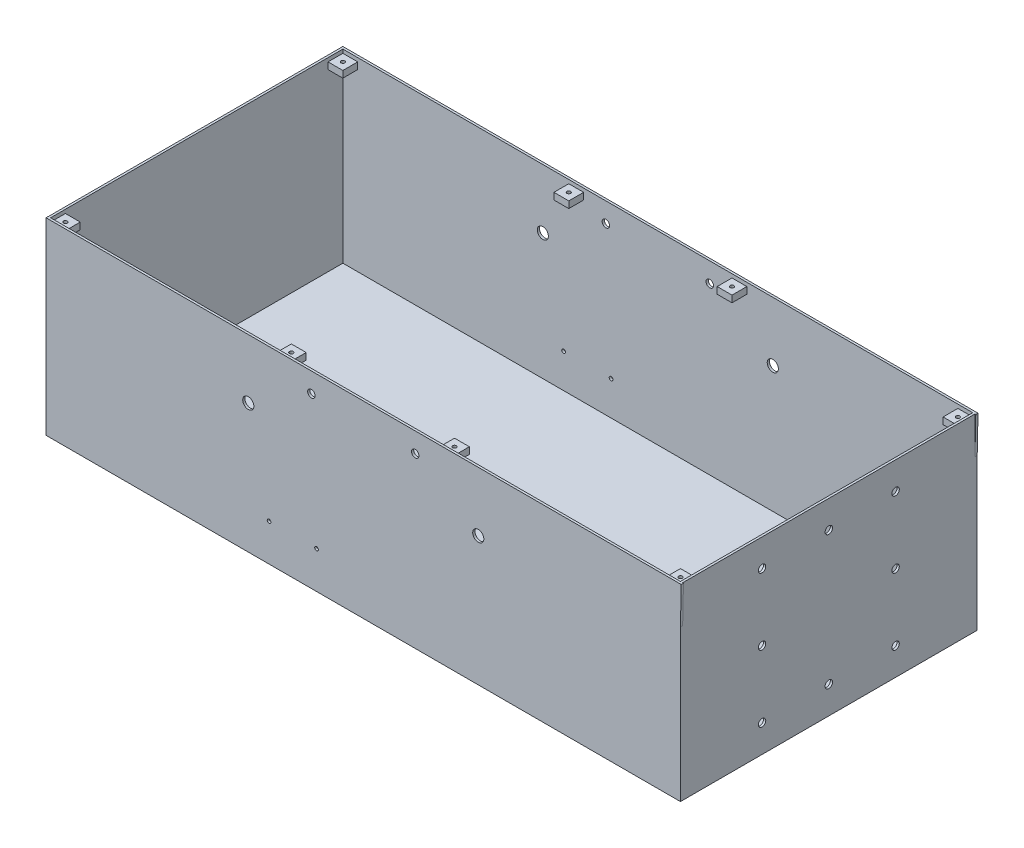
SolidWorks part; units mm, degrees
material "6061-T6 (SS)"
ref_plane "Front Plane" through (0, 0, 0) normal (0, 0, 1) x (1, 0, 0)
ref_plane "Top Plane" through (0, 0, 0) normal (0, 1, 0) x (1, 0, 0)
ref_plane "Right Plane" through (0, 0, 0) normal (1, 0, 0) x (0, 0, -1)
sketch "Sketch1" plane through (0, 0, 0) normal (0, 1, 0) x (1, 0, 0)
  line L1 (-427.5, 200) -> (427.5, 200)
  line L2 (-427.5, 200) -> (-427.5, -200)
  line L3 (-427.5, -200) -> (427.5, -200)
  line L4 (427.5, 200) -> (427.5, -200)
  line L5 (-427.5, 200) -> (427.5, -200) construction
  line L6 (-427.5, -200) -> (427.5, 200) construction
  point P0 (0, 0)
  dimension "D1" = 855
  dimension "D2" = 400
extrude "Boss-Extrude1" add sketch "Sketch1" along normal blind 4
sketch "Sketch3" plane through (0, 4, 0) normal (0, 1, 0) x (1, 0, 0)
  line L0 (-427.5, -200) -> (-427.5, -197)
  line L1 (-427.5, 200) -> (-427.5, -200) construction
  line L2 (-427.5, -197) -> (427.5, -197)
  line L3 (427.5, -200) -> (427.5, 200) construction
  line L4 (427.5, -197) -> (427.5, -200)
  line L5 (427.5, -200) -> (-427.5, -200)
  line L6 (-427.5, 200) -> (-424.5, 200)
  line L7 (427.5, 200) -> (-427.5, 200) construction
  line L8 (-424.5, 200) -> (-424.5, -197)
  line L9 (-424.5, -197) -> (-427.5, -197)
  line L10 (-427.5, 200) -> (-427.5, -197)
  line L11 (427.5, 200) -> (427.5, 197)
  line L12 (427.5, 197) -> (-424.5, 197)
  line L13 (-424.5, 197) -> (-424.5, 200)
  line L14 (-424.5, 200) -> (427.5, 200)
  line L15 (427.5, 197) -> (424.5, 197)
  line L16 (424.5, 197) -> (424.5, -197)
  line L17 (424.5, -197) -> (427.5, -197)
  line L18 (427.5, -197) -> (427.5, 197)
  line M8 (427.5, -200) -> (427.5, 200)
  line M9 (427.5, 200) -> (-427.5, 200)
  line M10 (-427.5, 200) -> (-427.5, -200)
  line M11 (-427.5, -200) -> (427.5, -200)
  dimension "D1" = 3
  dimension "D2" = 3
  dimension "D3" = 3
  dimension "D4" = 3
extrude "Boss-Extrude2" add sketch "Sketch3" along normal blind 200 contours L12 L8 M8 M9 | L12 L16 L2 M8 | L2 M10 M11 M8 | L8 L2 M9 M10
sketch "Sketch4" plane through (0, 0, 200) normal (0, 0, 1) x (1, 0, 0)
  line L0 (0, 254) -> (0, 204)
  line L1 (-427.5, 204) -> (427.5, 204) construction
  line L2 (-427.5, 204) -> (427.5, 204)
  arc A0 (-427.5, 204) -> (427.5, 204) centre (0, -1598.5625) cw
  line M7 (427.5, 204) -> (-427.5, 204)
  dimension "D1" = 50
extrude "Boss-Extrude3" add sketch "Sketch4" against normal blind 3 contours A0 L0 M7 | A0 L0 M7
sketch "Sketch6" plane through (0, 0, -200) normal (0, 0, -1) x (-1, 0, 0)
  line L0 (0, 254) -> (0, 204)
  line L1 (-427.5, 204) -> (427.5, 204) construction
  line L2 (-427.5, 204) -> (427.5, 204)
  arc A0 (-427.5, 204) -> (427.5, 204) centre (0, -1598.5625) cw
  line M4 (427.5, 204) -> (-427.5, 204)
  dimension "D1" = 50
extrude "Boss-Extrude4" add sketch "Sketch6" against normal blind 3 contours A0 L0 M4 | A0 L0 M4
sketch "Sketch10" plane through (0, 0, 200) normal (0, 0, 1) x (1, 0, 0)
  line L0 (-427.5, 204) -> (-427.5, 0) construction
  line L1 (427.5, 204) -> (427.5, 0) construction
  circle A0 centre (70, 227.5) radius 5
  circle A1 centre (-70, 227.5) radius 5
  dimension "D1" = 10
  dimension "D2" = 10
  dimension "D3" = 357.5
  dimension "D4" = 357.5
extrude "Cut-Extrude4" cut sketch "Sketch10" against normal through all
sketch "Sketch11" plane through (0, 0, 200) normal (0, 0, 1) x (1, 0, 0)
  circle A1 centre (-63, 50) radius 2.5
  circle A2 centre (-127, 50) radius 2.5
  dimension "D3" = 5
  dimension "D4" = 5
extrude "Cut-Extrude5" cut sketch "Sketch11" against normal through all
sketch "Sketch12" plane through (0, 0, 200) normal (0, 0, 1) x (1, 0, 0)
  line L0 (0, 254) -> (-427.6616, 254)
  line L1 (-427.6616, 254) -> (-427.5, 204)
  line L2 (0, 254) -> (428.5855, 254)
  line L3 (428.5855, 254) -> (427.5, 204)
  line L4 (-427.5, 204) -> (427.5, 204)
  line L7 (-427.5, 0) -> (427.5, 0)
  line L8 (427.5, 0) -> (427.5, 204)
  line L9 (-427.5, 204) -> (-427.5, 0)
  line L10 (-427.5, 0) -> (427.5, 0)
  line L11 (427.5, 0) -> (427.5, 204)
  line L12 (-427.5, 204) -> (-427.5, 0)
  arc A0 (427.5, 204) -> (-427.5, 204) centre (0, -1598.5625) ccw construction
  arc A2 (427.5, 204) -> (-427.5, 204) centre (0, -1598.5625) ccw
  arc M7 (427.5, 204) -> (-427.5, 204) centre (0, -1598.5625) ccw
  dimension "D1" = 0
extrude "Boss-Extrude7" add sketch "Sketch12" against normal blind 3 contours L3 L2 M7 | L0 L1 M7
sketch "Sketch23" plane through (0, 0, -200) normal (0, 0, -1) x (-1, 0, 0)
  line L0 (-427.5, 204) -> (-428.5855, 254)
  line L1 (-428.5855, 254) -> (0, 254)
  line L2 (0, 254) -> (427.6616, 254)
  line L3 (427.6616, 254) -> (427.5, 204)
  line L7 (-427.5, 0) -> (427.5, 0)
  line L8 (427.5, 0) -> (427.5, 204)
  line L9 (-427.5, 204) -> (-427.5, 0)
  line L10 (-427.5, 0) -> (427.5, 0)
  line L11 (427.5, 0) -> (427.5, 204)
  line L12 (-427.5, 204) -> (-427.5, 0)
  arc A0 (427.5, 204) -> (-427.5, 204) centre (0, -1598.5625) ccw construction
  arc A2 (427.5, 204) -> (-427.5, 204) centre (0, -1598.5625) ccw
  spline S0 degree 2 poles (-427.5, 204) (0, 304) (427.5, 204) knots 0 0 0 1 1 1
  arc M7 (427.5, 204) -> (-427.5, 204) centre (0, -1598.5625) ccw
  dimension "D1" = 0
extrude "Boss-Extrude10" add sketch "Sketch23" against normal blind 3 contours L1 L0 M7 | L3 L2 M7
sketch "Sketch33" plane through (0, 204, 0) normal (0, 1, 0) x (1, 0, 0)
  line L0 (-427.5, 197) -> (-424.5, 197)
  line L1 (-424.5, 197) -> (-424.5, -197)
  line L2 (-424.5, -197) -> (-427.5, -197)
  line L3 (-427.5, -197) -> (-427.5, 197)
extrude "Boss-Extrude14" add sketch "Sketch33" along normal blind 50
sketch "Sketch34" plane through (0, 204, 0) normal (0, 1, 0) x (1, 0, 0)
  line L0 (427.5, 197) -> (424.5, 197)
  line L1 (424.5, 197) -> (424.5, -197)
  line L2 (424.5, -197) -> (427.5, -197)
  line L3 (427.5, -197) -> (427.5, 197)
extrude "Boss-Extrude15" add sketch "Sketch34" along normal blind 50
ref_plane "Plane1" through (0, 240, 0) normal (0, 1, 0) x (1, 0, 0)
sketch "Sketch36" plane through (0, 240, 0) normal (0, 1, 0) x (1, 0, 0)
  line L0 (-424.5, 197) -> (-404.5, 197)
  line L1 (424.5, 197) -> (-424.5, 197) construction
  line L2 (-404.5, 197) -> (-404.5, 177)
  line L3 (-404.5, 177) -> (-424.5, 177)
  line L4 (-424.5, 197) -> (-424.5, -197) construction
  line L5 (-424.5, 177) -> (-424.5, 197)
  dimension "D1" = 20
  dimension "D2" = 20
extrude "Boss-Extrude16" add sketch "Sketch36" along normal blind 9
sketch "Sketch40" plane through (0, 254, 0) normal (0, 1, 0) x (1, 0, 0)
  line L0 (-424.5, 177) -> (-404.5, 177) construction
  line L1 (-404.5, 177) -> (-404.5, 197) construction
  circle A0 centre (-414.5, 187) radius 2.5
  dimension "D1" = 5
  dimension "D2" = 10
  dimension "D3" = 10
extrude "Cut-Extrude6" cut sketch "Sketch40" against normal blind 9
sketch "Sketch44" plane through (0, 240, 0) normal (0, 1, 0) x (1, 0, 0)
  line L0 (-424.5, -197) -> (-424.5, -177)
  line L1 (-424.5, 197) -> (-424.5, -197) construction
  line L2 (-424.5, -177) -> (-404.5, -177)
  line L3 (-404.5, -177) -> (-404.5, -197)
  line L4 (-424.5, -197) -> (424.5, -197) construction
  line L5 (-404.5, -197) -> (-424.5, -197)
  dimension "D1" = 20
  dimension "D2" = 20
extrude "Boss-Extrude18" add sketch "Sketch44" along normal blind 9
sketch "Sketch45" plane through (0, 254, 0) normal (0, 1, 0) x (1, 0, 0)
  line L0 (-404.5, -177) -> (-424.5, -177) construction
  line L1 (-404.5, -197) -> (-404.5, -177) construction
  circle A0 centre (-414.5, -187) radius 2.5
  dimension "D1" = 5
  dimension "D2" = 10
  dimension "D3" = 10
extrude "Cut-Extrude7" cut sketch "Sketch45" against normal blind 9
sketch "Sketch46" plane through (0, 240, 0) normal (0, 1, 0) x (1, 0, 0)
  line L0 (424.5, 197) -> (404.5, 197)
  line L1 (424.5, 197) -> (-424.5, 197) construction
  line L2 (404.5, 197) -> (404.5, 177)
  line L3 (404.5, 177) -> (424.5, 177)
  line L4 (424.5, 197) -> (424.5, -197) construction
  line L5 (424.5, 177) -> (424.5, 197)
  dimension "D1" = 20
  dimension "D2" = 20
extrude "Boss-Extrude19" add sketch "Sketch46" along normal blind 9
sketch "Sketch47" plane through (0, 254, 0) normal (0, 1, 0) x (1, 0, 0)
  line L0 (404.5, 177) -> (424.5, 177) construction
  line L1 (404.5, 197) -> (404.5, 177) construction
  circle A0 centre (414.5, 187) radius 2.5
  dimension "D1" = 5
  dimension "D2" = 10
  dimension "D3" = 10
extrude "Cut-Extrude8" cut sketch "Sketch47" against normal blind 9
sketch "Sketch48" plane through (0, 240, 0) normal (0, 1, 0) x (1, 0, 0)
  line L0 (424.5, -177) -> (404.5, -177)
  line L1 (424.5, 197) -> (424.5, -197) construction
  line L2 (404.5, -177) -> (404.5, -197)
  line L3 (-424.5, -197) -> (424.5, -197) construction
  line L4 (404.5, -197) -> (424.5, -197)
  line L5 (424.5, -197) -> (424.5, -177)
  dimension "D1" = 20
  dimension "D2" = 20
extrude "Boss-Extrude20" add sketch "Sketch48" along normal blind 9
sketch "Sketch49" plane through (0, 254, 0) normal (0, 1, 0) x (1, 0, 0)
  line L0 (424.5, -177) -> (404.5, -177) construction
  line L1 (404.5, -177) -> (404.5, -197) construction
  circle A0 centre (414.5, -187) radius 2.5
  dimension "D1" = 5
  dimension "D2" = 10
  dimension "D3" = 10
extrude "Cut-Extrude9" cut sketch "Sketch49" against normal blind 9
sketch "Sketch50" plane through (0, 240, 0) normal (0, 1, 0) x (1, 0, 0)
  line L0 (120, 197) -> (100, 197)
  line L1 (404.5, 197) -> (-404.5, 197) construction
  line L2 (100, 197) -> (100, 177)
  line L3 (100, 177) -> (120, 177)
  line L4 (120, 177) -> (120, 197)
  line L5 (427.5, -197) -> (427.5, 197) construction
  dimension "D1" = 20
  dimension "D2" = 20
  dimension "D3" = 327.5
extrude "Boss-Extrude21" add sketch "Sketch50" along normal blind 9
sketch "Sketch51" plane through (0, 254, 0) normal (0, 1, 0) x (1, 0, 0)
  line L0 (120, 177) -> (120, 197) construction
  line L1 (100, 177) -> (120, 177) construction
  circle A0 centre (110, 187) radius 2.5
  dimension "D1" = 5
  dimension "D2" = 10
  dimension "D3" = 10
extrude "Cut-Extrude10" cut sketch "Sketch51" against normal blind 9
sketch "Sketch52" plane through (0, 240, 0) normal (0, 1, 0) x (1, 0, 0)
  line L0 (100, -197) -> (100, -177)
  line L1 (-424.5, -197) -> (424.5, -197) construction
  line L2 (100, -177) -> (120, -177)
  line L3 (120, -177) -> (120, -197)
  line L4 (-404.5, -197) -> (404.5, -197) construction
  line L5 (120, -197) -> (100, -197)
  line L6 (427.5, -197) -> (427.5, 197) construction
  dimension "D1" = 20
  dimension "D2" = 20
  dimension "D3" = 327.5
extrude "Boss-Extrude22" add sketch "Sketch52" along normal blind 9
sketch "Sketch53" plane through (0, 254, 0) normal (0, 1, 0) x (1, 0, 0)
  line L0 (120, -177) -> (100, -177) construction
  line L1 (100, -177) -> (100, -197) construction
  circle A0 centre (110, -187) radius 2.5
  dimension "D1" = 5
  dimension "D2" = 10
  dimension "D3" = 10
extrude "Cut-Extrude11" cut sketch "Sketch53" against normal blind 9
sketch "Sketch58" plane through (0, 240, 0) normal (0, 1, 0) x (1, 0, 0)
  line L0 (-100, 197) -> (-120, 197)
  line L1 (424.5, 197) -> (-424.5, 197) construction
  line L2 (100, 197) -> (-404.5, 197) construction
  line L3 (-120, 197) -> (-120, 177)
  line L4 (-120, 177) -> (-100, 177)
  line L5 (-100, 177) -> (-100, 197)
  line L8 (-427.5, 197) -> (-427.5, -197) construction
  dimension "D1" = 20
  dimension "D2" = 20
  dimension "D3" = 327.5
extrude "Boss-Extrude25" add sketch "Sketch58" along normal blind 9
sketch "Sketch61" plane through (0, 254, 0) normal (0, 1, 0) x (1, 0, 0)
  line L0 (-120, 197) -> (-120, 177) construction
  line L1 (-120, 177) -> (-100, 177) construction
  circle A0 centre (-110, 187) radius 2.5
  dimension "D1" = 5
  dimension "D2" = 10
  dimension "D3" = 10
extrude "Cut-Extrude13" cut sketch "Sketch61" against normal blind 9
sketch "Sketch62" plane through (0, 240, 0) normal (0, 1, 0) x (1, 0, 0)
  line L0 (-100, -197) -> (-100, -177)
  line L1 (-424.5, -197) -> (424.5, -197) construction
  line L2 (-100, -177) -> (-120, -177)
  line L3 (-120, -177) -> (-120, -197)
  line L4 (-404.5, -197) -> (100, -197) construction
  line L5 (-120, -197) -> (-100, -197)
  line L6 (-427.5, 197) -> (-427.5, -197) construction
  dimension "D1" = 20
  dimension "D2" = 20
  dimension "D3" = 327.5
extrude "Boss-Extrude26" add sketch "Sketch62" along normal blind 9
sketch "Sketch63" plane through (0, 254, 0) normal (0, 1, 0) x (1, 0, 0)
  line L0 (-100, -177) -> (-120, -177) construction
  line L1 (-100, -197) -> (-100, -177) construction
  circle A0 centre (-110, -187) radius 2.5
  dimension "D1" = 5
  dimension "D2" = 10
  dimension "D3" = 10
  dimension "D4" = 10
extrude "Cut-Extrude14" cut sketch "Sketch63" against normal blind 9
sketch "Sketch64" plane through (0, 0, 200) normal (0, 0, 1) x (1, 0, 0)
  line L0 (-427.5, 204) -> (-427.5, 0) construction
  line L1 (427.5, 204) -> (427.5, 0) construction
  line L3 (-427.6616, 254) -> (428.5855, 254) construction
  circle A0 centre (155, 174) radius 7.5
  circle A1 centre (-155, 174) radius 7.5
  dimension "D1" = 15
  dimension "D2" = 15
  dimension "D3" = 272.5
  dimension "D4" = 272.5
  dimension "D5" = 80
  dimension "D6" = 80
extrude "Cut-Extrude15" cut sketch "Sketch64" against normal through all
sketch "Sketch65" plane through (427.5, 0, 0) normal (1, 0, 0) x (0, 0, -1)
  line L0 (-200, 204) -> (-200, 0) construction
  line L1 (200, 204) -> (200, 0) construction
  line L2 (-200, 0) -> (200, 0) construction
  circle A0 centre (90, 217) radius 5
  circle A1 centre (0, 217) radius 5
  circle A2 centre (-90, 217) radius 5
  circle A3 centre (-90, 127) radius 5
  circle A5 centre (90, 127) radius 5
  circle A6 centre (90, 37) radius 5
  circle A7 centre (0, 37) radius 5
  circle A8 centre (-90, 37) radius 5
  dimension "D1" = 10
  dimension "D2" = 110
  dimension "D3" = 90
  dimension "D4" = 90
  dimension "D5" = 110
  dimension "D6" = 110
  dimension "D7" = 110
  dimension "D8" = 110
  dimension "D9" = 110
  dimension "D10" = 90
  dimension "D11" = 90
  dimension "D12" = 90
  dimension "D13" = 180
  dimension "D14" = 90
  dimension "D15" = 37
  dimension "D16" = 90
extrude "Cut-Extrude16" cut sketch "Sketch65" against normal blind 3
